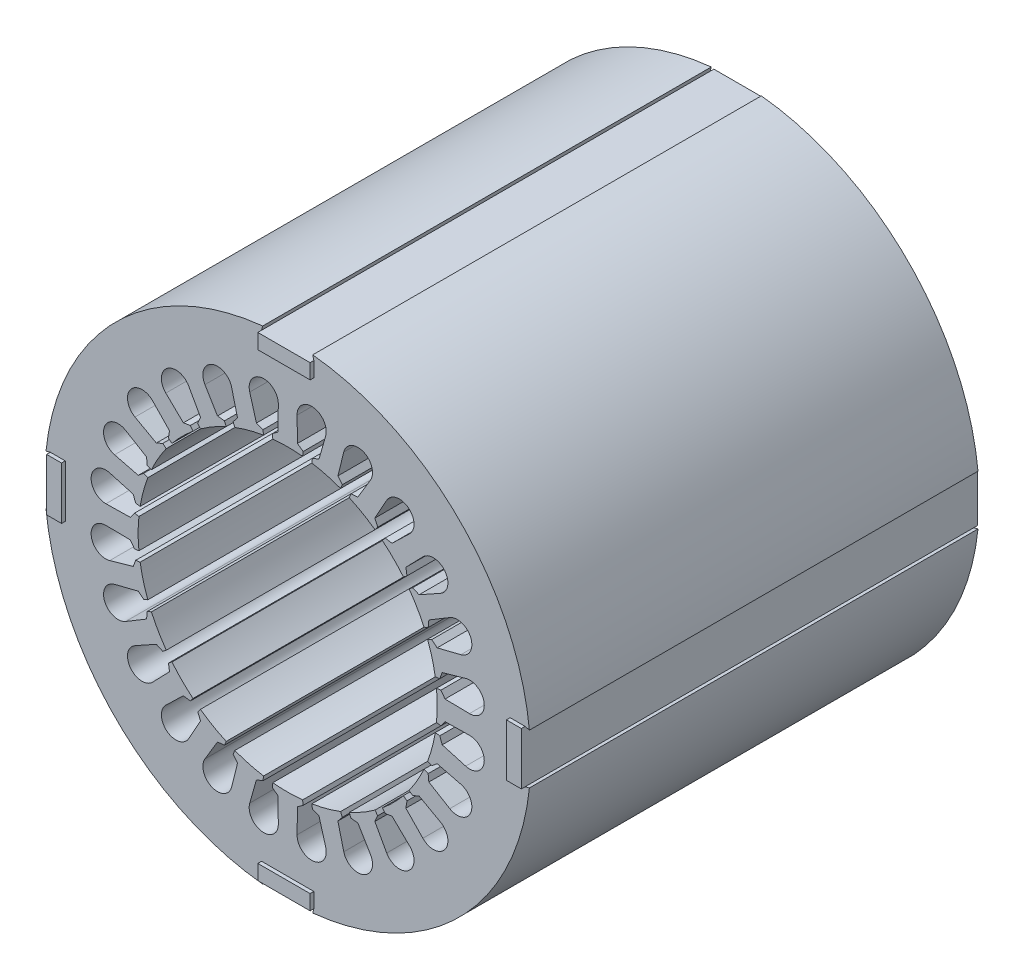
SolidWorks part; units mm, degrees
ref_plane "前视基准面" through (0, 0, 0) normal (0, 0, 1) x (1, 0, 0)
ref_plane "上视基准面" through (0, 0, 0) normal (0, 1, 0) x (1, 0, 0)
ref_plane "右视基准面" through (0, 0, 0) normal (1, 0, 0) x (0, 0, -1)
sketch "草图1" plane through (0, 0, 0) normal (0, 0, 1) x (1, 0, 0)
  line L0 (2.5094, 48.6164) -> (2.6158, 42.0867)
  line L1 (10.159, 47.6093) -> (8.3662, 41.3296)
  line L2 (4.1359, 40.9919) -> (2.6158, 42.0867)
  line L3 (-6.4578, 39.4753) -> (-6.6145, 40.6656)
  line L4 (-3.9792, 39.8016) -> (-4.1359, 40.9919)
  line L5 (6.6145, 40.6656) -> (8.3662, 41.3296)
  line L6 (6.4578, 39.4753) -> (6.6145, 40.6656)
  line L7 (-4.1359, 40.9919) -> (-2.6158, 42.0867)
  line L8 (-2.5094, 48.6164) -> (-2.6158, 42.0867)
  line L9 (3.9792, 39.8016) -> (4.1359, 40.9919)
  line L10 (-10.159, 47.6093) -> (-8.3662, 41.3296)
  line L11 (-6.6145, 40.6656) -> (-8.3662, 41.3296)
  line L12 (15.0067, 46.3103) -> (13.4195, 39.9756)
  line L13 (22.135, 43.3577) -> (18.778, 37.756)
  line L14 (14.6044, 38.5247) -> (13.4195, 39.9756)
  line L15 (16.9141, 37.568) -> (18.778, 37.756)
  line L16 (16.4547, 36.4588) -> (16.9141, 37.568)
  line L17 (14.145, 37.4155) -> (14.6044, 38.5247)
  line L18 (26.4814, 40.8483) -> (23.3087, 35.1402)
  line L19 (32.6026, 36.1514) -> (27.9101, 31.6094)
  line L20 (24.0777, 33.4321) -> (23.3087, 35.1402)
  line L21 (26.0611, 31.9102) -> (27.9101, 31.6094)
  line L22 (25.3303, 30.9577) -> (26.0611, 31.9102)
  line L23 (23.3469, 32.4796) -> (24.0777, 33.4321)
  line L24 (36.1514, 32.6026) -> (31.6094, 27.9101)
  line L25 (40.8483, 26.4814) -> (35.1402, 23.3087)
  line L26 (31.9102, 26.0611) -> (31.6094, 27.9101)
  line L27 (33.4321, 24.0777) -> (35.1402, 23.3087)
  line L28 (32.4796, 23.3469) -> (33.4321, 24.0777)
  line L29 (30.9577, 25.3303) -> (31.9102, 26.0611)
  line L30 (43.3577, 22.135) -> (37.756, 18.778)
  line L31 (46.3103, 15.0067) -> (39.9756, 13.4195)
  line L32 (37.568, 16.9141) -> (37.756, 18.778)
  line L33 (38.5247, 14.6044) -> (39.9756, 13.4195)
  line L34 (37.4155, 14.145) -> (38.5247, 14.6044)
  line L35 (36.4588, 16.4547) -> (37.568, 16.9141)
  line L36 (47.6093, 10.159) -> (41.3296, 8.3662)
  line L37 (48.6164, 2.5094) -> (42.0867, 2.6158)
  line L38 (40.6656, 6.6145) -> (41.3296, 8.3662)
  line L39 (40.9919, 4.1359) -> (42.0867, 2.6158)
  line L40 (39.8016, 3.9792) -> (40.9919, 4.1359)
  line L41 (39.4753, 6.4578) -> (40.6656, 6.6145)
  line L42 (48.6164, -2.5094) -> (42.0867, -2.6158)
  line L43 (47.6093, -10.159) -> (41.3296, -8.3662)
  line L44 (40.9919, -4.1359) -> (42.0867, -2.6158)
  line L45 (40.6656, -6.6145) -> (41.3296, -8.3662)
  line L46 (39.4753, -6.4578) -> (40.6656, -6.6145)
  line L47 (39.8016, -3.9792) -> (40.9919, -4.1359)
  line L48 (46.3103, -15.0067) -> (39.9756, -13.4195)
  line L49 (43.3577, -22.135) -> (37.756, -18.778)
  line L50 (38.5247, -14.6044) -> (39.9756, -13.4195)
  line L51 (37.568, -16.9141) -> (37.756, -18.778)
  line L52 (36.4588, -16.4547) -> (37.568, -16.9141)
  line L53 (37.4155, -14.145) -> (38.5247, -14.6044)
  line L54 (40.8483, -26.4814) -> (35.1402, -23.3087)
  line L55 (36.1514, -32.6026) -> (31.6094, -27.9101)
  line L56 (33.4321, -24.0777) -> (35.1402, -23.3087)
  line L57 (31.9102, -26.0611) -> (31.6094, -27.9101)
  line L58 (30.9577, -25.3303) -> (31.9102, -26.0611)
  line L59 (32.4796, -23.3469) -> (33.4321, -24.0777)
  line L60 (32.6026, -36.1514) -> (27.9101, -31.6094)
  line L61 (26.4814, -40.8483) -> (23.3087, -35.1402)
  line L62 (26.0611, -31.9102) -> (27.9101, -31.6094)
  line L63 (24.0777, -33.4321) -> (23.3087, -35.1402)
  line L64 (23.3469, -32.4796) -> (24.0777, -33.4321)
  line L65 (25.3303, -30.9577) -> (26.0611, -31.9102)
  line L66 (22.135, -43.3577) -> (18.778, -37.756)
  line L67 (15.0067, -46.3103) -> (13.4195, -39.9756)
  line L68 (16.9141, -37.568) -> (18.778, -37.756)
  line L69 (14.6044, -38.5247) -> (13.4195, -39.9756)
  line L70 (14.145, -37.4155) -> (14.6044, -38.5247)
  line L71 (16.4547, -36.4588) -> (16.9141, -37.568)
  line L72 (10.159, -47.6093) -> (8.3662, -41.3296)
  line L73 (2.5094, -48.6164) -> (2.6158, -42.0867)
  line L74 (6.6145, -40.6656) -> (8.3662, -41.3296)
  line L75 (4.1359, -40.9919) -> (2.6158, -42.0867)
  line L76 (3.9792, -39.8016) -> (4.1359, -40.9919)
  line L77 (6.4578, -39.4753) -> (6.6145, -40.6656)
  line L78 (-2.5094, -48.6164) -> (-2.6158, -42.0867)
  line L79 (-10.159, -47.6093) -> (-8.3662, -41.3296)
  line L80 (-4.1359, -40.9919) -> (-2.6158, -42.0867)
  line L81 (-6.6145, -40.6656) -> (-8.3662, -41.3296)
  line L82 (-6.4578, -39.4753) -> (-6.6145, -40.6656)
  line L83 (-3.9792, -39.8016) -> (-4.1359, -40.9919)
  line L84 (-15.0067, -46.3103) -> (-13.4195, -39.9756)
  line L85 (-22.135, -43.3577) -> (-18.778, -37.756)
  line L86 (-14.6044, -38.5247) -> (-13.4195, -39.9756)
  line L87 (-16.9141, -37.568) -> (-18.778, -37.756)
  line L88 (-16.4547, -36.4588) -> (-16.9141, -37.568)
  line L89 (-14.145, -37.4155) -> (-14.6044, -38.5247)
  line L90 (-26.4814, -40.8483) -> (-23.3087, -35.1402)
  line L91 (-32.6026, -36.1514) -> (-27.9101, -31.6094)
  line L92 (-24.0777, -33.4321) -> (-23.3087, -35.1402)
  line L93 (-26.0611, -31.9102) -> (-27.9101, -31.6094)
  line L94 (-25.3303, -30.9577) -> (-26.0611, -31.9102)
  line L95 (-23.3469, -32.4796) -> (-24.0777, -33.4321)
  line L96 (-36.1514, -32.6026) -> (-31.6094, -27.9101)
  line L97 (-40.8483, -26.4814) -> (-35.1402, -23.3087)
  line L98 (-31.9102, -26.0611) -> (-31.6094, -27.9101)
  line L99 (-33.4321, -24.0777) -> (-35.1402, -23.3087)
  line L100 (-32.4796, -23.3469) -> (-33.4321, -24.0777)
  line L101 (-30.9577, -25.3303) -> (-31.9102, -26.0611)
  line L102 (-43.3577, -22.135) -> (-37.756, -18.778)
  line L103 (-46.3103, -15.0067) -> (-39.9756, -13.4195)
  line L104 (-37.568, -16.9141) -> (-37.756, -18.778)
  line L105 (-38.5247, -14.6044) -> (-39.9756, -13.4195)
  line L106 (-37.4155, -14.145) -> (-38.5247, -14.6044)
  line L107 (-36.4588, -16.4547) -> (-37.568, -16.9141)
  line L108 (-47.6093, -10.159) -> (-41.3296, -8.3662)
  line L109 (-48.6164, -2.5094) -> (-42.0867, -2.6158)
  line L110 (-40.6656, -6.6145) -> (-41.3296, -8.3662)
  line L111 (-40.9919, -4.1359) -> (-42.0867, -2.6158)
  line L112 (-39.8016, -3.9792) -> (-40.9919, -4.1359)
  line L113 (-39.4753, -6.4578) -> (-40.6656, -6.6145)
  line L114 (-48.6164, 2.5094) -> (-42.0867, 2.6158)
  line L115 (-47.6093, 10.159) -> (-41.3296, 8.3662)
  line L116 (-40.9919, 4.1359) -> (-42.0867, 2.6158)
  line L117 (-40.6656, 6.6145) -> (-41.3296, 8.3662)
  line L118 (-39.4753, 6.4578) -> (-40.6656, 6.6145)
  line L119 (-39.8016, 3.9792) -> (-40.9919, 4.1359)
  line L120 (-46.3103, 15.0067) -> (-39.9756, 13.4195)
  line L121 (-43.3577, 22.135) -> (-37.756, 18.778)
  line L122 (-38.5247, 14.6044) -> (-39.9756, 13.4195)
  line L123 (-37.568, 16.9141) -> (-37.756, 18.778)
  line L124 (-36.4588, 16.4547) -> (-37.568, 16.9141)
  line L125 (-37.4155, 14.145) -> (-38.5247, 14.6044)
  line L126 (-40.8483, 26.4814) -> (-35.1402, 23.3087)
  line L127 (-36.1514, 32.6026) -> (-31.6094, 27.9101)
  line L128 (-33.4321, 24.0777) -> (-35.1402, 23.3087)
  line L129 (-31.9102, 26.0611) -> (-31.6094, 27.9101)
  line L130 (-30.9577, 25.3303) -> (-31.9102, 26.0611)
  line L131 (-32.4796, 23.3469) -> (-33.4321, 24.0777)
  line L132 (-32.6026, 36.1514) -> (-27.9101, 31.6094)
  line L133 (-26.4814, 40.8483) -> (-23.3087, 35.1402)
  line L134 (-26.0611, 31.9102) -> (-27.9101, 31.6094)
  line L135 (-24.0777, 33.4321) -> (-23.3087, 35.1402)
  line L136 (-23.3469, 32.4796) -> (-24.0777, 33.4321)
  line L137 (-25.3303, 30.9577) -> (-26.0611, 31.9102)
  line L138 (-22.135, 43.3577) -> (-18.778, 37.756)
  line L139 (-15.0067, 46.3103) -> (-13.4195, 39.9756)
  line L140 (-16.9141, 37.568) -> (-18.778, 37.756)
  line L141 (-14.6044, 38.5247) -> (-13.4195, 39.9756)
  line L142 (-14.145, 37.4155) -> (-14.6044, 38.5247)
  line L143 (-16.4547, 36.4588) -> (-16.9141, 37.568)
  line L144 (63.5, 7) -> (64.6547, 6.6906)
  line L145 (7, 63.5) -> (6.6906, 64.6547)
  line L146 (-7, 63.5) -> (-6.6906, 64.6547)
  line L147 (-7, 63.5) -> (7, 63.5)
  line L148 (63.5, 7) -> (63.5, -7)
  line L149 (63.5, -7) -> (64.6547, -6.6906)
  line L150 (7, -63.5) -> (6.6906, -64.6547)
  line L151 (7, -63.5) -> (-7, -63.5)
  line L152 (-7, -63.5) -> (-6.6906, -64.6547)
  line L153 (-63.5, -7) -> (-64.6547, -6.6906)
  line L154 (-63.5, -7) -> (-63.5, 7)
  line L155 (-63.5, 7) -> (-64.6547, 6.6906)
  arc A0 (-6.4578, 39.4753) -> (-14.145, 37.4155) centre (0, 0) ccw
  arc A1 (-6.6906, 64.6547) -> (-64.6547, 6.6906) centre (0, 0) ccw
  arc A2 (10.159, 47.6093) -> (2.5094, 48.6164) centre (6.4088, 48.6799) ccw
  arc A3 (-2.5094, 48.6164) -> (-10.159, 47.6093) centre (-6.4088, 48.6799) ccw
  arc A4 (22.135, 43.3577) -> (15.0067, 46.3103) centre (18.7898, 45.3625) ccw
  arc A5 (32.6026, 36.1514) -> (26.4814, 40.8483) centre (29.8902, 38.9536) ccw
  arc A6 (40.8483, 26.4814) -> (36.1514, 32.6026) centre (38.9536, 29.8902) ccw
  arc A7 (46.3103, 15.0067) -> (43.3577, 22.135) centre (45.3625, 18.7898) ccw
  arc A8 (48.6164, 2.5094) -> (47.6093, 10.159) centre (48.6799, 6.4088) ccw
  arc A9 (47.6093, -10.159) -> (48.6164, -2.5094) centre (48.6799, -6.4088) ccw
  arc A10 (43.3577, -22.135) -> (46.3103, -15.0067) centre (45.3625, -18.7898) ccw
  arc A11 (36.1514, -32.6026) -> (40.8483, -26.4814) centre (38.9536, -29.8902) ccw
  arc A12 (26.4814, -40.8483) -> (32.6026, -36.1514) centre (29.8902, -38.9536) ccw
  arc A13 (15.0067, -46.3103) -> (22.135, -43.3577) centre (18.7898, -45.3625) ccw
  arc A14 (2.5094, -48.6164) -> (10.159, -47.6093) centre (6.4088, -48.6799) ccw
  arc A15 (-10.159, -47.6093) -> (-2.5094, -48.6164) centre (-6.4088, -48.6799) ccw
  arc A16 (-22.135, -43.3577) -> (-15.0067, -46.3103) centre (-18.7898, -45.3625) ccw
  arc A17 (-32.6026, -36.1514) -> (-26.4814, -40.8483) centre (-29.8902, -38.9536) ccw
  arc A18 (-40.8483, -26.4814) -> (-36.1514, -32.6026) centre (-38.9536, -29.8902) ccw
  arc A19 (-46.3103, -15.0067) -> (-43.3577, -22.135) centre (-45.3625, -18.7898) ccw
  arc A20 (-48.6164, -2.5094) -> (-47.6093, -10.159) centre (-48.6799, -6.4088) ccw
  arc A21 (-47.6093, 10.159) -> (-48.6164, 2.5094) centre (-48.6799, 6.4088) ccw
  arc A22 (-43.3577, 22.135) -> (-46.3103, 15.0067) centre (-45.3625, 18.7898) ccw
  arc A23 (-36.1514, 32.6026) -> (-40.8483, 26.4814) centre (-38.9536, 29.8902) ccw
  arc A24 (-26.4814, 40.8483) -> (-32.6026, 36.1514) centre (-29.8902, 38.9536) ccw
  arc A25 (-15.0067, 46.3103) -> (-22.135, 43.3577) centre (-18.7898, 45.3625) ccw
  arc A26 (-25.3303, 30.9577) -> (-30.9577, 25.3303) centre (0, 0) ccw
  arc A27 (-16.4547, 36.4588) -> (-23.3469, 32.4796) centre (0, 0) ccw
  arc A28 (3.9792, 39.8016) -> (-3.9792, 39.8016) centre (0, 0) ccw
  arc A29 (14.145, 37.4155) -> (6.4578, 39.4753) centre (0, 0) ccw
  arc A30 (23.3469, 32.4796) -> (16.4547, 36.4588) centre (0, 0) ccw
  arc A31 (30.9577, 25.3303) -> (25.3303, 30.9577) centre (0, 0) ccw
  arc A32 (36.4588, 16.4547) -> (32.4796, 23.3469) centre (0, 0) ccw
  arc A33 (39.4753, 6.4578) -> (37.4155, 14.145) centre (0, 0) ccw
  arc A34 (39.8016, -3.9792) -> (39.8016, 3.9792) centre (0, 0) ccw
  arc A35 (37.4155, -14.145) -> (39.4753, -6.4578) centre (0, 0) ccw
  arc A36 (32.4796, -23.3469) -> (36.4588, -16.4547) centre (0, 0) ccw
  arc A37 (25.3303, -30.9577) -> (30.9577, -25.3303) centre (0, 0) ccw
  arc A38 (16.4547, -36.4588) -> (23.3469, -32.4796) centre (0, 0) ccw
  arc A39 (6.4578, -39.4753) -> (14.145, -37.4155) centre (0, 0) ccw
  arc A40 (-3.9792, -39.8016) -> (3.9792, -39.8016) centre (0, 0) ccw
  arc A41 (-14.145, -37.4155) -> (-6.4578, -39.4753) centre (0, 0) ccw
  arc A42 (-23.3469, -32.4796) -> (-16.4547, -36.4588) centre (0, 0) ccw
  arc A43 (-30.9577, -25.3303) -> (-25.3303, -30.9577) centre (0, 0) ccw
  arc A44 (-36.4588, -16.4547) -> (-32.4796, -23.3469) centre (0, 0) ccw
  arc A45 (-39.4753, -6.4578) -> (-37.4155, -14.145) centre (0, 0) ccw
  arc A46 (-39.8016, 3.9792) -> (-39.8016, -3.9792) centre (0, 0) ccw
  arc A47 (-37.4155, 14.145) -> (-39.4753, 6.4578) centre (0, 0) ccw
  arc A48 (-32.4796, 23.3469) -> (-36.4588, 16.4547) centre (0, 0) ccw
  arc A49 (-64.6547, -6.6906) -> (-6.6906, -64.6547) centre (0, 0) ccw
  arc A50 (6.6906, -64.6547) -> (64.6547, -6.6906) centre (0, 0) ccw
  arc A51 (64.6547, 6.6906) -> (6.6906, 64.6547) centre (0, 0) ccw
extrude "拉伸1" add sketch "草图1" along normal blind 120
sketch "草图2" plane through (0, 0, 120) normal (0, 0, 1) x (1, 0, 0)
  line L0 (-7, 63.5) -> (-7, 59.5)
  line L1 (-7, 59.5) -> (7, 59.5)
  line L2 (7, 59.5) -> (7, 63.5)
  line L3 (7, 63.5) -> (-7, 63.5)
  line L4 (63.5, 7) -> (59.5, 7)
  line L5 (63.5, -7) -> (63.5, 7)
  line L6 (59.5, 7) -> (59.5, -7)
  line L7 (59.5, -7) -> (63.5, -7)
  line L8 (7, -63.5) -> (7, -59.5)
  line L9 (-7, -63.5) -> (7, -63.5)
  line L10 (7, -59.5) -> (-7, -59.5)
  line L11 (-7, -59.5) -> (-7, -63.5)
  line L12 (-63.5, -7) -> (-59.5, -7)
  line L13 (-63.5, 7) -> (-63.5, -7)
  line L14 (-59.5, -7) -> (-59.5, 7)
  line L15 (-59.5, 7) -> (-63.5, 7)
  dimension "D1" = 4
extrude "拉伸2" add sketch "草图2" along normal blind 1
sketch "草图3" plane through (0, 0, 0) normal (0, 0, -1) x (-1, 0, 0)
  line L0 (-7, 63.5) -> (-7, 59.5)
  line L1 (-7, 59.5) -> (7, 59.5)
  line L2 (7, 59.5) -> (7, 63.5)
  line L3 (7, 63.5) -> (-7, 63.5)
  line L4 (63.5, -7) -> (63.5, 7)
  line L5 (59.5, 7) -> (59.5, -7)
  line L6 (63.5, 7) -> (59.5, 7)
  line L7 (59.5, -7) -> (63.5, -7)
  line L8 (-7, -63.5) -> (7, -63.5)
  line L9 (7, -59.5) -> (-7, -59.5)
  line L10 (7, -63.5) -> (7, -59.5)
  line L11 (-7, -59.5) -> (-7, -63.5)
  line L12 (-63.5, 7) -> (-63.5, -7)
  line L13 (-59.5, -7) -> (-59.5, 7)
  line L14 (-63.5, -7) -> (-59.5, -7)
  line L15 (-59.5, 7) -> (-63.5, 7)
  dimension "D1" = 4
extrude "拉伸3" add sketch "草图3" along normal blind 1
scale "缩放比例1" scale about origin uniform scaling yes scale factor 0.25
